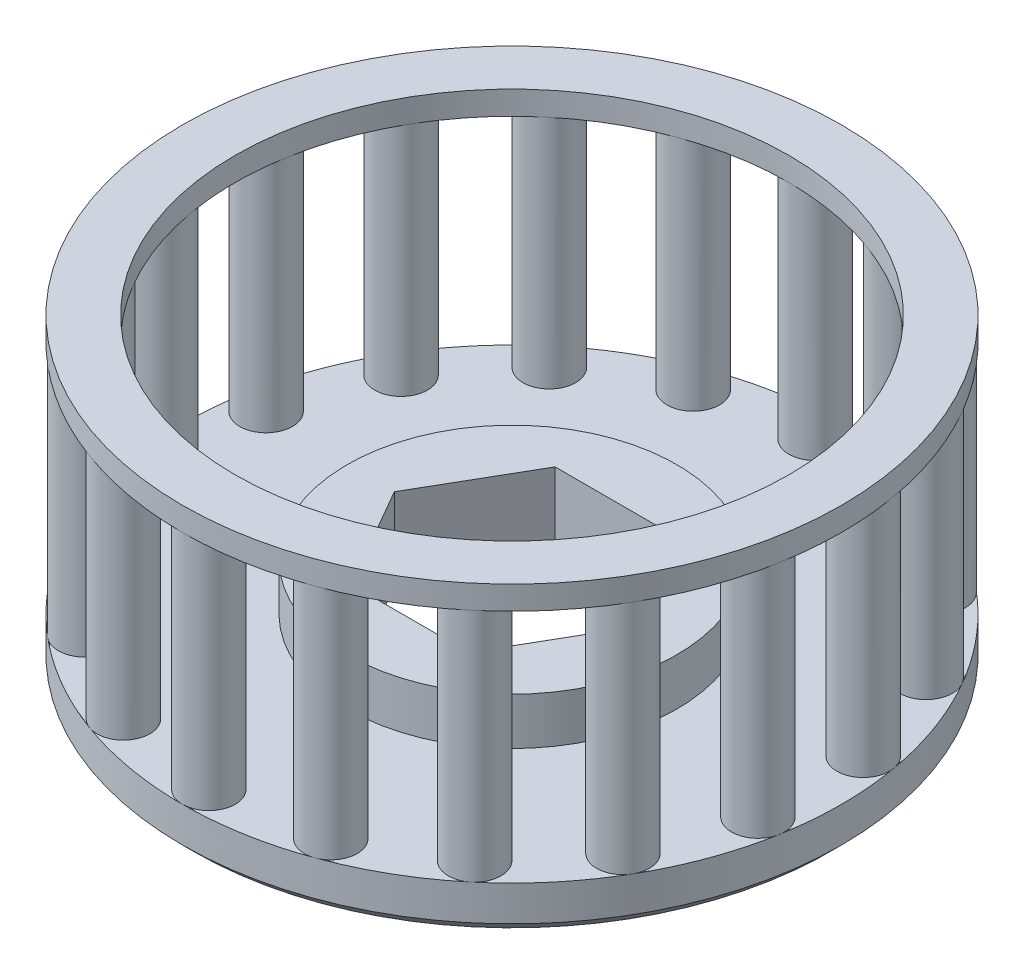
SolidWorks part; units mm, degrees
ref_plane "Front Plane" through (0, 0, 0) normal (0, 0, 1) x (1, 0, 0)
ref_plane "Top Plane" through (0, 0, 0) normal (0, 1, 0) x (1, 0, 0)
ref_plane "Right Plane" through (0, 0, 0) normal (1, 0, 0) x (0, 0, -1)
sketch "Sketch1" plane through (0, 0, 0) normal (0, 1, 0) x (1, 0, 0)
  line L1 (5, 0) -> (2.5, 4.3301)
  line L2 (2.5, 4.3301) -> (-2.5, 4.3301)
  line L3 (-2.5, 4.3301) -> (-5, 0)
  line L4 (-5, 0) -> (-2.5, -4.3301)
  line L5 (-2.5, -4.3301) -> (2.5, -4.3301)
  line L6 (2.5, -4.3301) -> (5, 0)
  circle A0 centre (0, 0) radius 4.3301 construction
  circle A1 centre (0, 0) radius 14
  point P10 (-3.75, -2.1651)
  dimension "D2" = 28
  dimension "D1" = 10
  dimension "D3" = 8.6603
extrude "Boss-Extrude1" add sketch "Sketch1" along normal blind 2
sketch "Sketch2" plane through (0, 2, 0) normal (0, 1, 0) x (1, 0, 0)
  line L0 (0, 0) -> (0, 14) construction
  circle A0 centre (0, 0) radius 14 construction
  circle A1 centre (0, 12.88) radius 1.12
  circle A2 centre (2.2366, 12.6843) radius 1.12
  circle A3 centre (4.4052, 12.1032) radius 1.12
  circle A4 centre (6.44, 11.1544) radius 1.12
  circle A5 centre (8.2791, 9.8667) radius 1.12
  circle A6 centre (9.8667, 8.2791) radius 1.12
  circle A7 centre (11.1544, 6.44) radius 1.12
  circle A8 centre (12.1032, 4.4052) radius 1.12
  circle A9 centre (12.6843, 2.2366) radius 1.12
  circle A10 centre (12.88, 0) radius 1.12
  circle A11 centre (12.6843, -2.2366) radius 1.12
  circle A12 centre (12.1032, -4.4052) radius 1.12
  circle A13 centre (11.1544, -6.44) radius 1.12
  circle A14 centre (9.8667, -8.2791) radius 1.12
  circle A15 centre (8.2791, -9.8667) radius 1.12
  circle A16 centre (6.44, -11.1544) radius 1.12
  circle A17 centre (4.4052, -12.1032) radius 1.12
  circle A18 centre (2.2366, -12.6843) radius 1.12
  circle A19 centre (0, -12.88) radius 1.12
  circle A20 centre (-2.2366, -12.6843) radius 1.12
  circle A21 centre (-4.4052, -12.1032) radius 1.12
  circle A22 centre (-6.44, -11.1544) radius 1.12
  circle A23 centre (-8.2791, -9.8667) radius 1.12
  circle A24 centre (-9.8667, -8.2791) radius 1.12
  circle A25 centre (-11.1544, -6.44) radius 1.12
  circle A26 centre (-12.1032, -4.4052) radius 1.12
  circle A27 centre (-12.6843, -2.2366) radius 1.12
  circle A28 centre (-12.88, 0) radius 1.12
  circle A29 centre (-12.6843, 2.2366) radius 1.12
  circle A30 centre (-12.1032, 4.4052) radius 1.12
  circle A31 centre (-11.1544, 6.44) radius 1.12
  circle A32 centre (-9.8667, 8.2791) radius 1.12
  circle A33 centre (-8.2791, 9.8667) radius 1.12
  circle A34 centre (-6.44, 11.1544) radius 1.12
  circle A35 centre (-4.4052, 12.1032) radius 1.12
  circle A36 centre (-2.2366, 12.6843) radius 1.12
  point P47 (0, 0)
  dimension "D1" = 2.24
  dimension "D2" = 36
extrude "Boss-Extrude2" add sketch "Sketch2" along normal blind 10 contours L0 A1 | A1 L0 | A3 | A5 | A7 | A9 | A11 | A13 | A15 | A17 | A21 | A23 | A25 | A27 | A29 | A31 | A33 | A35 | A19
sketch "Sketch3" plane through (0, 12, 0) normal (0, 1, 0) x (1, 0, 0)
  circle A0 centre (0, 0) radius 14
  circle A1 centre (0, 0) radius 11.76
  dimension "D1" = 28
  dimension "D2" = 23.52
extrude "Boss-Extrude3" add sketch "Sketch3" along normal blind 1
chamfer "Chamfer1" distance 0.5 angle 45 7 edges at (0, 0, 14) (0, 0, 4.3301) (-3.75, 0, 2.1651) (-3.75, 0, -2.1651) (0, 0, -4.3301) (3.75, 0, -2.1651) (3.75, 0, 2.1651)
sketch "Sketch5" plane through (0, 2, 0) normal (0, 1, 0) x (1, 0, 0)
  line L1 (5, 0) -> (2.5, 4.3301)
  line L2 (2.5, 4.3301) -> (-2.5, 4.3301)
  line L3 (-2.5, 4.3301) -> (-5, 0)
  line L4 (-5, 0) -> (-2.5, -4.3301)
  line L5 (-2.5, -4.3301) -> (2.5, -4.3301)
  line L6 (2.5, -4.3301) -> (5, 0)
  circle A0 centre (0, 0) radius 4.3301 construction
  circle A1 centre (0, 0) radius 7
  dimension "D1" = 14
extrude "Boss-Extrude4" add sketch "Sketch5" along normal blind 2
